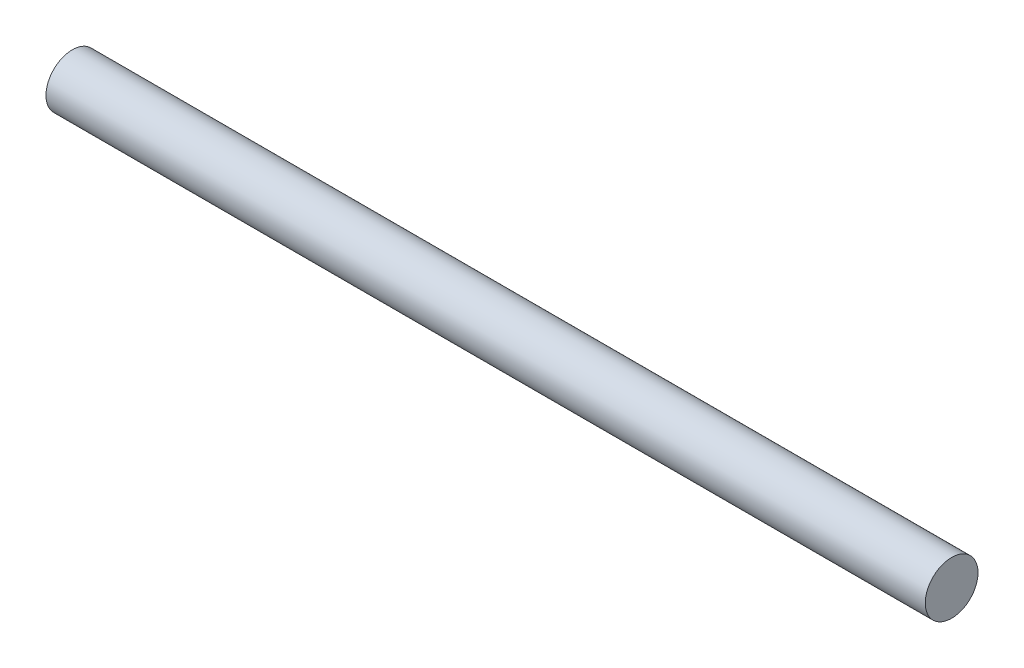
SolidWorks part; units mm, degrees
material "Stainless Steel (ferritic)"
ref_plane "Front Plane" through (0, 0, 0) normal (0, 0, 1) x (1, 0, 0)
ref_plane "Top Plane" through (0, 0, 0) normal (0, 1, 0) x (1, 0, 0)
ref_plane "Right Plane" through (0, 0, 0) normal (1, 0, 0) x (0, 0, -1)
sketch "Sketch1" plane through (0, 0, 0) normal (1, 0, 0) x (0, 0, -1)
  circle A0 centre (0, 0) radius 30
extrude "Boss-Extrude1" add sketch "Sketch1" along normal blind 1000
